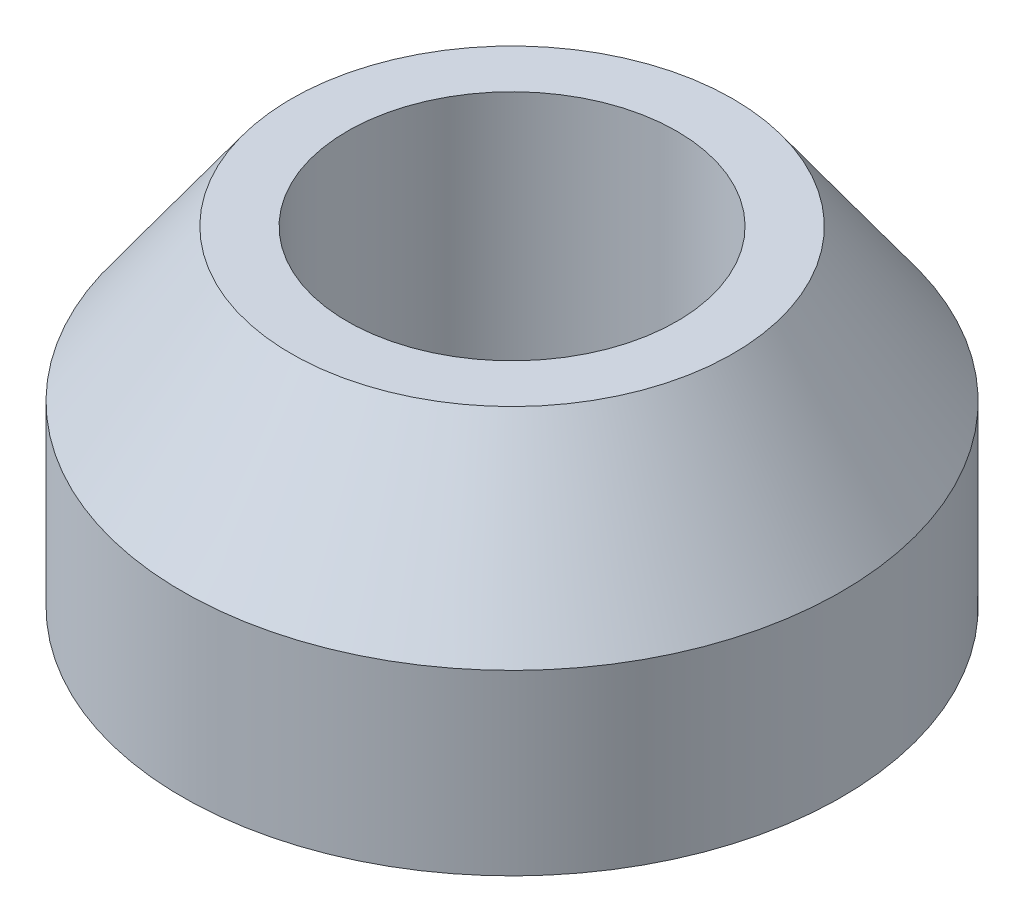
SolidWorks part; units mm, degrees
material "AISI 4130 Steel, normalized at 870C"
ref_plane "Front Plane" through (0, 0, 0) normal (0, 0, 1) x (1, 0, 0)
ref_plane "Top Plane" through (0, 0, 0) normal (0, 1, 0) x (1, 0, 0)
ref_plane "Right Plane" through (0, 0, 0) normal (1, 0, 0) x (0, 0, -1)
sketch "Sketch2" plane through (0, 0, 0) normal (1, 0, 0) x (0, 0, -1)
  line L0 (0, 0) -> (3.175, 0) construction
  line L1 (3.175, 0) -> (3.175, 6.35)
  line L2 (3.175, 6.35) -> (4.2545, 6.35)
  line L3 (4.2545, 6.35) -> (6.35, 3.429)
  line L4 (6.35, 3.429) -> (6.35, 0)
  line L5 (6.35, 0) -> (3.175, 0)
  line L6 (0, 0) -> (0, 6.35) construction
  dimension "D1" = 3.175
  dimension "D2" = 6.35
  dimension "D3" = 3.175
  dimension "D4" = 3.429
  dimension "D5" = 1.0795
revolve "Revolve1" add sketch "Sketch2" angle 360 about L6
equation "\"A\"= .25'From FE13 Sus Cost List \"ebay\""
equation "\"B\"= .335"
equation "\"C\"= .5"
equation "\"D\" = .25"
equation "\"E\"= .135"
equation "\"F\"= 35"
equation "\"D1@Sketch2\"=\"A\"/2"
equation "\"D2@Sketch2\"=\"D\""
equation "\"D3@Sketch2\"=(\"C\"-\"A\")/2"
equation "\"D4@Sketch2\"=\"E\""
equation "\"D5@Sketch2\"=(\"B\"-\"A\")/2"
